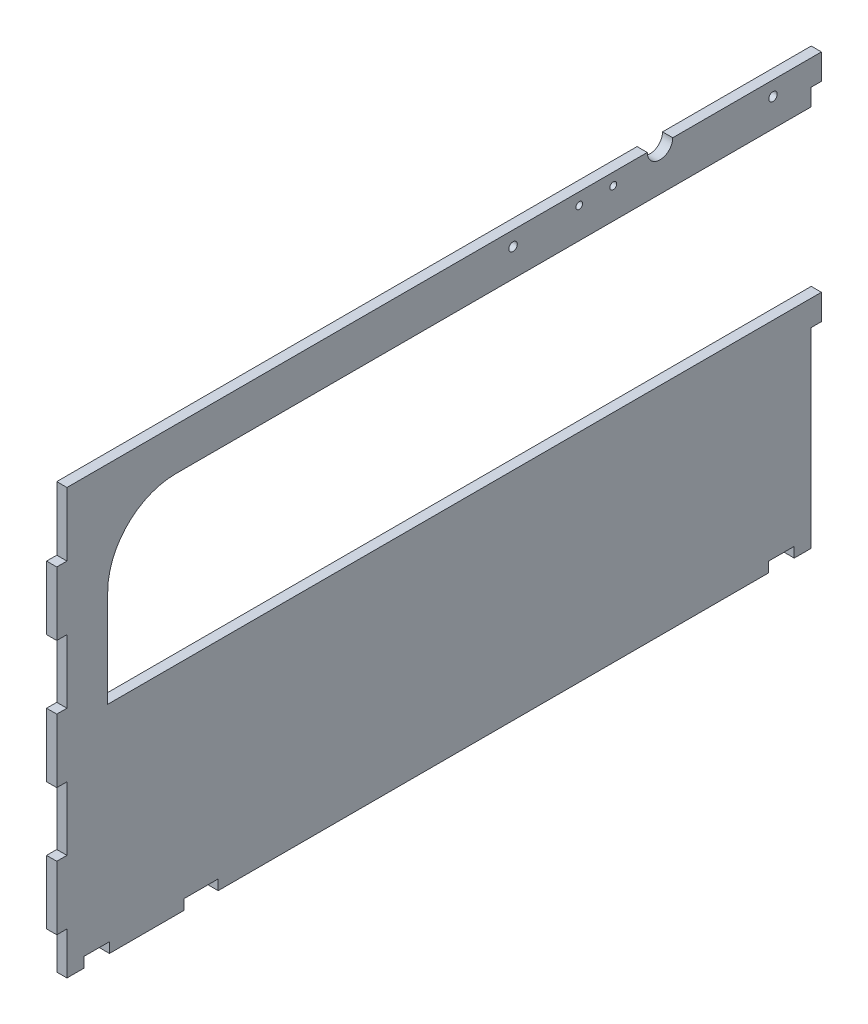
SolidWorks part; units mm, degrees
ref_plane "Front" through (0, 0, 0) normal (0, 0, 1) x (1, 0, 0)
ref_plane "Top" through (0, 0, 0) normal (0, 1, 0) x (1, 0, 0)
ref_plane "Right" through (0, 0, 0) normal (1, 0, 0) x (0, 0, -1)
sketch "Sketch1" plane through (0, 0, 0) normal (1, 0, 0) x (0, 0, -1)
  line L0 (450, 225) -> (450, 250)
  line L1 (0, 0) -> (450, 0)
  line L2 (0, 0) -> (0, 250)
  line L3 (0, 250) -> (450, 250)
  line L4 (450, 0) -> (450, 127.5)
  line L5 (450, 225) -> (30, 225)
  line L7 (450, 127.5) -> (30, 127.5)
  line L8 (30, 225) -> (30, 127.5)
  dimension "D1" = 420
  dimension "D2" = 250
  dimension "D3" = 127.5
  dimension "D4" = 25
  dimension "D5" = 30
extrude "Boss-Extrude1" add sketch "Sketch1" along normal blind 6
sketch "Sketch2" plane through (6, 0, 0) normal (1, 0, 0) x (0, 0, -1)
  line L1 (0, 250) -> (6, 250)
  line L2 (0, 250) -> (0, 212.5)
  line L3 (0, 212.5) -> (6, 212.5)
  line L4 (6, 250) -> (6, 212.5)
  dimension "D1" = 6
  dimension "D2" = 37.5
extrude "Cut-Extrude1" cut sketch "Sketch2" against normal blind 6
pattern_linear "LPattern1" count 4 spacing 75 along (0, -1, 0) of "Cut-Extrude1"
fillet "Fillet1" radius 40 1 edges at (3, 225, -30)
sketch "Sketch3" plane through (0, 0, 0) normal (-1, 0, 0) x (0, 0, 1)
  line L0 (-450, 0) -> (-450, 127.5) construction
  line L1 (-450, 235) -> (-444, 235)
  line L2 (-450, 235) -> (-450, 225)
  line L3 (-450, 225) -> (-444, 225)
  line L4 (-444, 235) -> (-444, 225)
  line L5 (-70, 225) -> (-450, 225) construction
  line L7 (-450, 112.5) -> (-444, 112.5)
  line L8 (-450, 112.5) -> (-450, 0)
  line L9 (-450, 0) -> (-444, 0)
  line L10 (-444, 112.5) -> (-444, 0)
  line L12 (-450, 225) -> (-450, 250) construction
  line L13 (-450, 127.5) -> (-30, 127.5) construction
  line L14 (-6, 0) -> (-450, 0) construction
  dimension "D1" = 6
  dimension "D2" = 10
  dimension "D4" = 15
extrude "Cut-Extrude2" cut sketch "Sketch3" against normal through all
sketch "Sketch4" plane through (0, 0, 0) normal (-1, 0, 0) x (0, 0, 1)
  line L0 (-6, 0) -> (-444, 0) construction
  line L1 (-16, 0) -> (-31, 0)
  line L2 (-16, 0) -> (-16, 6)
  line L3 (-16, 6) -> (-31, 6)
  line L4 (-31, 0) -> (-31, 6)
  line L5 (-6, 62.5) -> (-6, 100) construction
  line L6 (-6, 0) -> (-444, 0) construction
  line L7 (-434, 0) -> (-419, 0)
  line L8 (-434, 0) -> (-434, 6)
  line L9 (-434, 6) -> (-419, 6)
  line L10 (-419, 0) -> (-419, 6)
  line L11 (-444, 0) -> (-444, 112.5) construction
  dimension "D1" = 10
  dimension "D2" = 15
  dimension "D3" = 6
  dimension "D4" = 10
extrude "Cut-Extrude3" cut sketch "Sketch4" against normal through all
sketch "Sketch5" plane through (0, 0, 0) normal (-1, 0, 0) x (0, 0, 1)
  line L0 (-450, 235) -> (-450, 250) construction
  line L1 (-450, 250) -> (-6, 250) construction
  line L2 (-362.5, 250) -> (-347.5, 250)
  line L3 (-444, 235) -> (-450, 235) construction
  circle A0 centre (-327.5, 243) radius 2
  circle A1 centre (-307.5, 243) radius 2
  arc A3 (-362.5, 250) -> (-347.5, 250) centre (-355, 250) ccw
  dimension "D3" = 4
  dimension "D5" = 95
  dimension "D6" = 7.5
  dimension "D1" = 122.5
  dimension "D2" = 7
  dimension "D4" = 20
  dimension "D7" = 15
extrude "Cut-Extrude4" cut sketch "Sketch5" against normal through all
sketch "Sketch6" plane through (0, 0, 0) normal (-1, 0, 0) x (0, 0, 1)
  line L0 (-31, 0) -> (-419, 0) construction
  line L1 (-75, 0) -> (-95, 0)
  line L2 (-75, 0) -> (-75, 6)
  line L3 (-75, 6) -> (-95, 6)
  line L4 (-95, 0) -> (-95, 6)
  line L6 (-16, 6) -> (-31, 6) construction
  line L7 (0, 62.5) -> (0, 25) construction
  dimension "D1" = 20
  dimension "D2" = 75
extrude "Cut-Extrude5" cut sketch "Sketch6" against normal through all
sketch "Sketch7" plane through (0, 0, 0) normal (-1, 0, 0) x (0, 0, 1)
  line L0 (-450, 235) -> (-450, 250) construction
  line L1 (-450, 250) -> (-362.5, 250) construction
  circle A0 centre (-421.5, 241.5) radius 2.5
  circle A1 centre (-268.51, 241.5) radius 2.5
  point P6 (0, 0)
  point P7 (0, 0)
  dimension "D4" = 5
  dimension "D1" = 28.5
  dimension "D2" = 181.49
  dimension "D3" = 8.5
extrude "Cut-Extrude6" cut sketch "Sketch7" against normal through all
